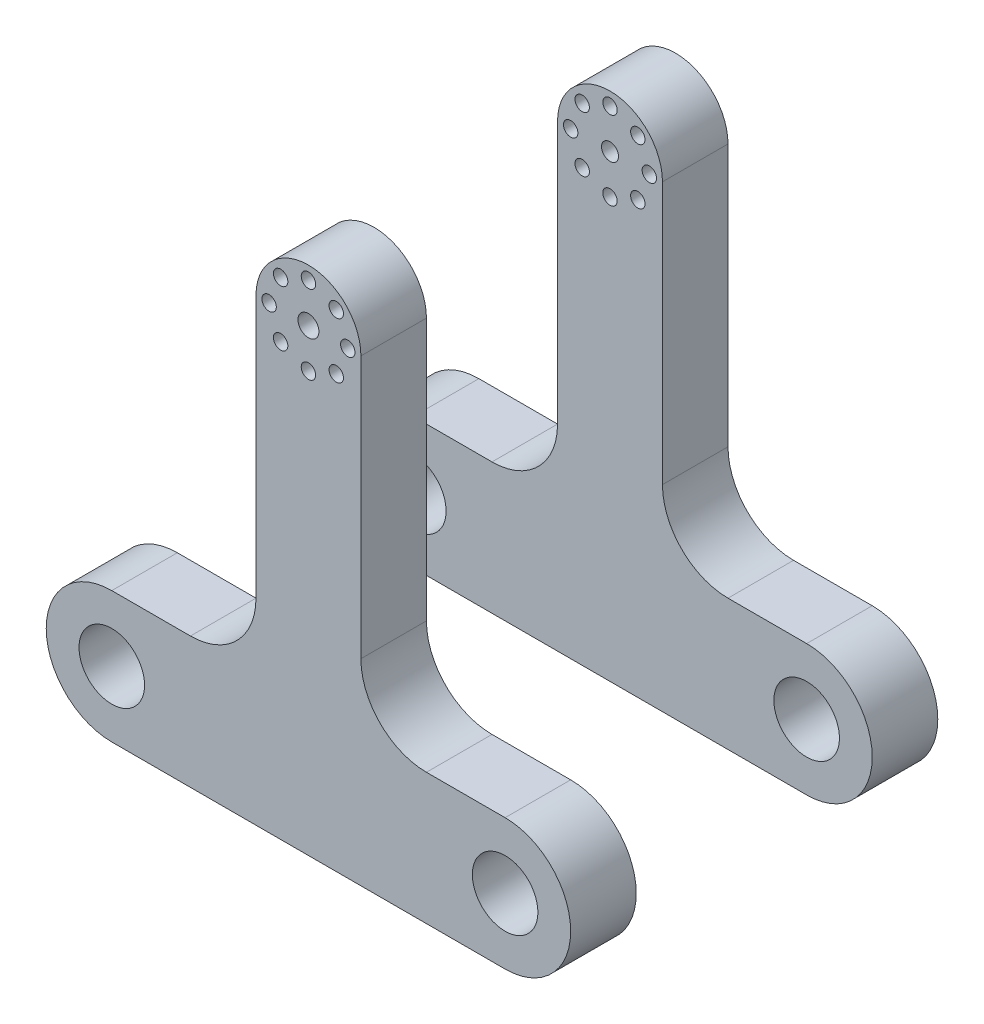
SolidWorks part; units mm, degrees
material "ABS"
ref_plane "正面" through (0, 0, 0) normal (0, 0, 1) x (1, 0, 0)
ref_plane "平面" through (0, 0, 0) normal (0, 1, 0) x (1, 0, 0)
ref_plane "右側面" through (0, 0, 0) normal (1, 0, 0) x (0, 0, -1)
sketch "ｽｹｯﾁ1" plane through (0, 0, 0) normal (0, 0, 1) x (1, 0, 0)
  line L0 (0, 68) -> (0, 60) construction
  line L1 (-30, 0) -> (30, 0) construction
  line L2 (-30, 10) -> (-18, 10)
  line L3 (-8, 20) -> (-8, 60)
  line L4 (8, 60) -> (8, 20)
  line L5 (18, 10) -> (30, 10)
  line L6 (-30, -10) -> (30, -10)
  line L7 (0, 0) -> (0, 60) construction
  arc A0 (8, 60) -> (-8, 60) centre (0, 60) ccw
  circle A1 centre (-30, 0) radius 5
  circle A2 centre (30, 0) radius 5
  arc A3 (-30, 10) -> (-30, -10) centre (-30, 0) ccw
  arc A4 (30, -10) -> (30, 10) centre (30, 0) ccw
  circle A5 centre (0, 60) radius 1.6
  arc A6 (-18, 10) -> (-8, 20) centre (-18, 20) ccw
  arc A7 (8, 20) -> (18, 10) centre (18, 20) ccw
  dimension "D1" = 16
  dimension "D2" = 10
  dimension "D3" = 10
  dimension "D6" = 20
  dimension "D7" = 3.2
  dimension "D8" = 10
  dimension "D4" = 60
  dimension "D5" = 60
extrude "ﾎﾞｽ - 押し出し1" add sketch "ｽｹｯﾁ1" along normal blind 10
sketch "ｽｹｯﾁ2" plane through (0, 0, 10) normal (0, 0, 1) x (1, 0, 0)
  circle A0 centre (0, 60) radius 6 construction
  circle A1 centre (0, 66) radius 1.1
  circle A2 centre (4.2426, 64.2426) radius 1.1
  circle A3 centre (6, 60) radius 1.1
  circle A4 centre (4.2426, 55.7574) radius 1.1
  circle A5 centre (0, 54) radius 1.1
  circle A6 centre (-4.2426, 55.7574) radius 1.1
  circle A7 centre (-6, 60) radius 1.1
  circle A8 centre (-4.2426, 64.2426) radius 1.1
  point P5 (-8.1329, 84.9155)
  point P6 (0, 0)
  point P22 (0, 60)
  dimension "D1" = 12
  dimension "D2" = 2.2
  dimension "D3" = 8
extrude "ｶｯﾄ - 押し出し1" cut sketch "ｽｹｯﾁ2" against normal through all
ref_plane "平面1" through (0, 0, -36) normal (0, 0, -1) x (-1, 0, 0)
sketch "ｽｹｯﾁ4" plane through (0, 0, -36) normal (0, 0, -1) x (-1, 0, 0)
  line L5 (30, 10) -> (18, 10)
  line L6 (-30, -10) -> (30, -10)
  line L7 (-18, 10) -> (-30, 10)
  line L8 (-8, 60) -> (-8, 20)
  line L9 (8, 20) -> (8, 60)
  line L10 (30, 10) -> (18, 10)
  line L11 (-30, -10) -> (30, -10)
  line L12 (-18, 10) -> (-30, 10)
  line L13 (-8, 60) -> (-8, 20)
  line L14 (8, 20) -> (8, 60)
  circle A0 centre (-4.2426, 64.2426) radius 1.1 construction
  circle A1 centre (30, 0) radius 5
  circle A2 centre (30, 0) radius 5
  circle A3 centre (-30, 0) radius 5
  circle A4 centre (-30, 0) radius 5
  circle A5 centre (-6, 60) radius 1.1 construction
  circle A6 centre (-4.2426, 55.7574) radius 1.1 construction
  circle A7 centre (0, 54) radius 1.1 construction
  circle A8 centre (4.2426, 55.7574) radius 1.1 construction
  circle A9 centre (6, 60) radius 1.1 construction
  circle A10 centre (4.2426, 64.2426) radius 1.1 construction
  circle A11 centre (0, 66) radius 1.1 construction
  circle A13 centre (-4.2426, 64.2426) radius 1.1
  circle A14 centre (-6, 60) radius 1.1
  circle A15 centre (-4.2426, 55.7574) radius 1.1
  circle A16 centre (0, 54) radius 1.1
  circle A17 centre (4.2426, 55.7574) radius 1.1
  circle A18 centre (6, 60) radius 1.1
  circle A19 centre (4.2426, 64.2426) radius 1.1
  circle A20 centre (0, 66) radius 1.1
  circle A21 centre (0, 60) radius 1.3
  circle A22 centre (0, 60) radius 1.6 construction
  arc A28 (8, 20) -> (18, 10) centre (18, 20) ccw
  arc A29 (30, -10) -> (30, 10) centre (30, 0) ccw
  arc A30 (-30, 10) -> (-30, -10) centre (-30, 0) ccw
  arc A31 (-18, 10) -> (-8, 20) centre (-18, 20) ccw
  arc A32 (8, 60) -> (-8, 60) centre (0, 60) ccw
  arc A33 (8, 20) -> (18, 10) centre (18, 20) ccw
  arc A34 (30, -10) -> (30, 10) centre (30, 0) ccw
  arc A35 (-30, 10) -> (-30, -10) centre (-30, 0) ccw
  arc A36 (-18, 10) -> (-8, 20) centre (-18, 20) ccw
  arc A37 (8, 60) -> (-8, 60) centre (0, 60) ccw
  dimension "D3" = 2.6
  dimension "D1" = 0
  dimension "D2" = 0
  dimension "D4" = 0
extrude "ﾎﾞｽ - 押し出し2" add sketch "ｽｹｯﾁ4" along normal blind 10 separate body
